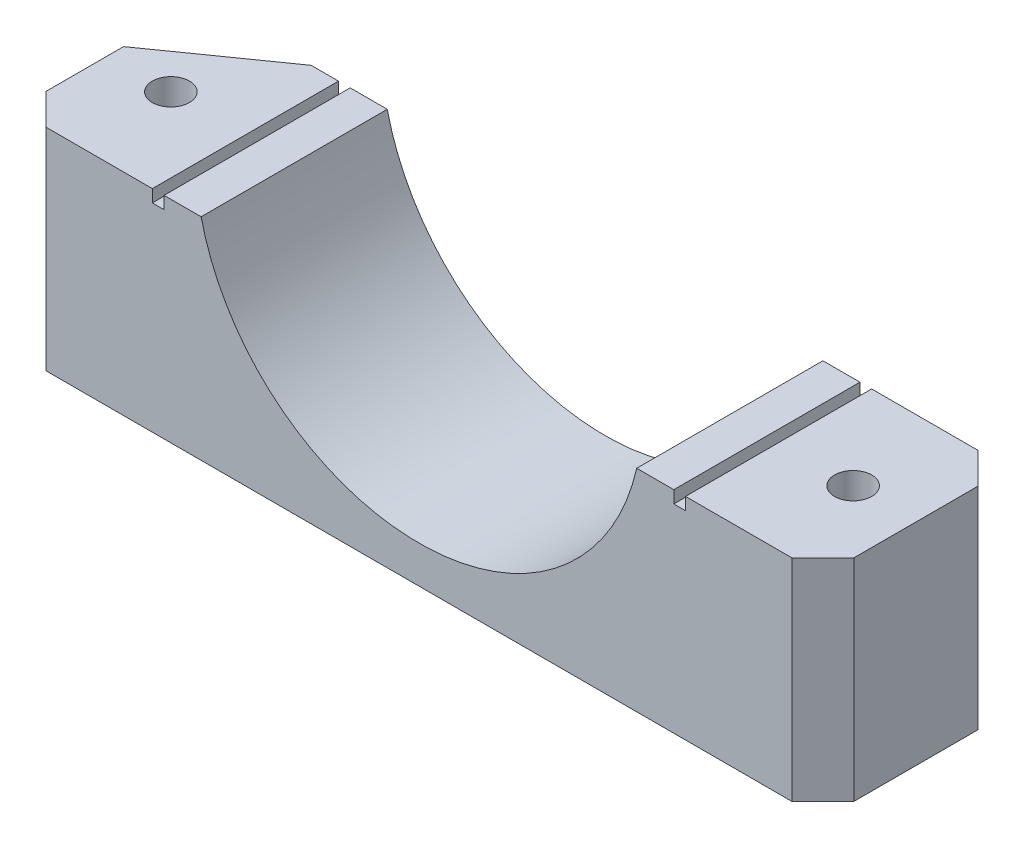
SolidWorks part; units mm, degrees
ref_plane "Front Plane" through (0, 0, 0) normal (0, 0, 1) x (1, 0, 0)
ref_plane "Top Plane" through (0, 0, 0) normal (0, 1, 0) x (1, 0, 0)
ref_plane "Right Plane" through (0, 0, 0) normal (1, 0, 0) x (0, 0, -1)
sketch "Sketch1" plane through (0, 0, 0) normal (0, 0, 1) x (1, 0, 0)
  line L0 (-17.5499, -4) -> (-32.5499, -4)
  line L1 (-32.5499, -4) -> (-32.5499, -21)
  line L2 (-32.5499, -21) -> (32.5499, -21)
  line L3 (32.5499, -21) -> (32.5499, -4)
  line L4 (32.5499, -4) -> (17.5499, -4)
  arc A0 (-17.5499, -4) -> (17.5499, -4) centre (0, 0) ccw
  dimension "D1" = 18
  dimension "D2" = 15
  dimension "D3" = 15
  dimension "D4" = 21
  dimension "D5" = 4
extrude "Boss-Extrude1" add sketch "Sketch1" along normal blind 15 contours L4 A0 L0 L1 L2 L3
chamfer "Chamfer1" distance 2.5 3 edges at (32.5499, -12.5, 0) (32.5499, -12.5, 15) (-32.5499, -12.5, 15)
sketch "Sketch2" plane through (0, -4, 0) normal (0, 1, 0) x (1, 0, 0)
  line L0 (0, -8.25) -> (0, 8.25) construction
  circle A0 centre (27.4886, -7.5) radius 1.5
  circle A1 centre (-27.4886, -7.5) radius 1.5
  dimension "D1" = 3
extrude "Cut-Extrude1" cut sketch "Sketch2" against normal through all
sketch "Sketch3" plane through (0, -4, 0) normal (0, 1, 0) x (1, 0, 0)
  line L0 (-17.5499, 0) -> (-32.5499, 0) construction
  line L1 (-21.4797, 0) -> (-20.5371, 0)
  line L2 (-21.4797, 0) -> (-21.4797, -15)
  line L3 (-21.4797, -15) -> (-20.5371, -15)
  line L4 (-20.5371, 0) -> (-20.5371, -15)
  line L5 (-17.5499, -15) -> (-30.0499, -15) construction
extrude "Cut-Extrude2" cut sketch "Sketch3" against normal blind 1 contours L2 L1 L4 L3
mirror "Mirror1" about plane through (0, 0, 0) normal (1, 0, 0) of "Cut-Extrude2"
sketch "Sketch4" plane through (0, -21, 0) normal (0, -1, 0) x (1, 0, 0)
  line L0 (-23.6831, 0) -> (-32.5499, 6.25)
  line L1 (-32.5499, 0) -> (30.0499, 0) construction
  line L2 (-32.5499, 12.5) -> (-32.5499, 0) construction
  line L3 (-32.5499, 6.25) -> (-32.5499, 0)
  line L4 (-32.5499, 0) -> (-23.6831, 0)
extrude "Cut-Extrude3" cut sketch "Sketch4" against normal blind 25
